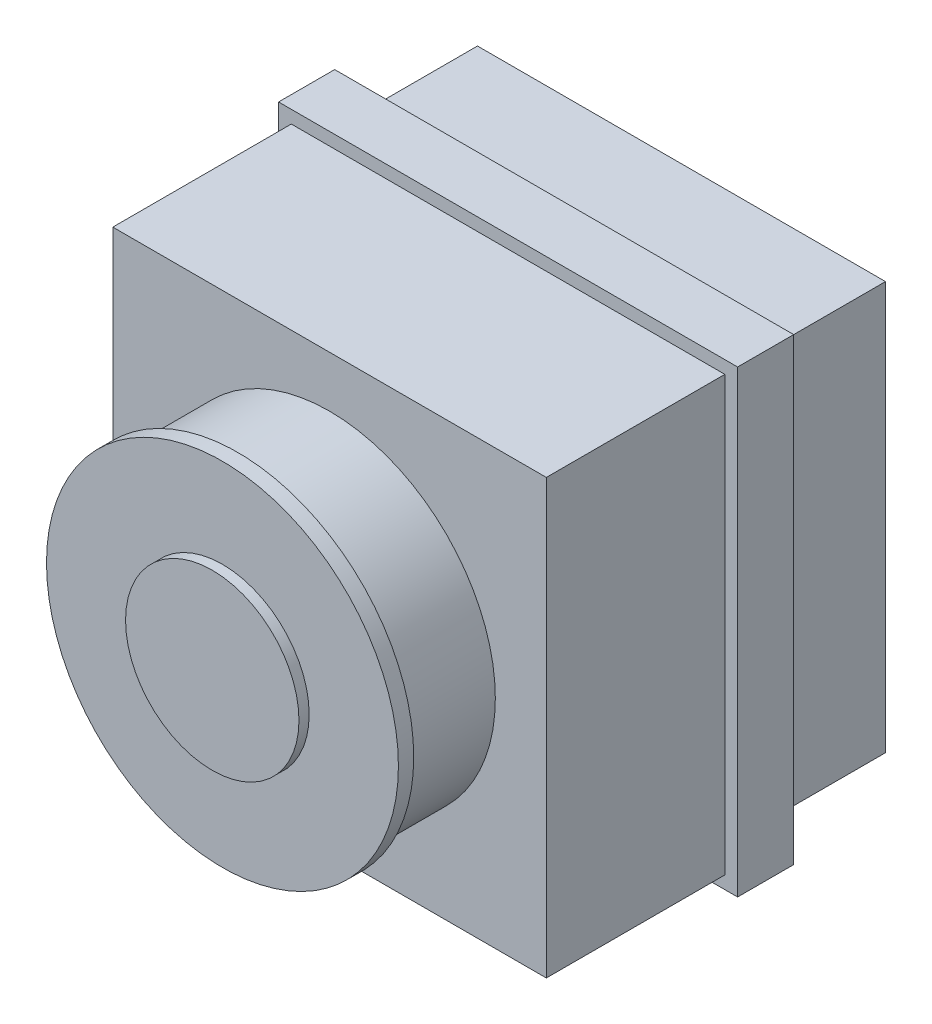
SolidWorks part; units mm, degrees
ref_plane "前基準面" through (0, 0, 0) normal (0, 0, 1) x (1, 0, 0)
ref_plane "上基準面" through (0, 0, 0) normal (0, 1, 0) x (1, 0, 0)
ref_plane "右基準面" through (0, 0, 0) normal (1, 0, 0) x (0, 0, -1)
sketch "草圖1" plane through (0, 0, 0) normal (0, 0, 1) x (1, 0, 0)
  line L0 (26, -29) -> (34, -29)
  line L1 (34, -29) -> (34, -21)
  line L2 (34, -21) -> (26, -21)
  line L3 (26, -21) -> (26, -29)
extrude "foam pad" add sketch "草圖1" along normal blind 2.3
sketch "草圖2" plane through (0, 0, 0) normal (0, 0, 1) x (1, 0, 0)
  line L0 (25.5, -29.5) -> (34.5, -29.5)
  line L1 (34.5, -29.5) -> (34.5, -20.5)
  line L2 (34.5, -20.5) -> (25.5, -20.5)
  line L3 (25.5, -20.5) -> (25.5, -29.5)
extrude "sensor PCB" add sketch "草圖2" along normal blind 1.1 from offset 2.3
sketch "草圖3" plane through (0, 0, 0) normal (0, 0, 1) x (1, 0, 0)
  line L0 (25.75, -29.25) -> (34.25, -29.25)
  line L1 (34.25, -29.25) -> (34.25, -20.75)
  line L2 (34.25, -20.75) -> (25.75, -20.75)
  line L3 (25.75, -20.75) -> (25.75, -29.25)
extrude "lens holder" add sketch "草圖3" along normal blind 3.5 from offset 3.4
sketch "草圖4" plane through (0, 0, 0) normal (0, 0, 1) x (1, 0, 0)
  circle A0 centre (30, -25) radius 3.25
extrude "lens barrel" add sketch "草圖4" along normal blind 1.8 from offset 6.9
sketch "草圖5" plane through (0, 0, 0) normal (0, 0, 1) x (1, 0, 0)
  circle A0 centre (30, -25) radius 3.45
extrude "lens ring" add sketch "草圖5" along normal blind 0.3 from offset 8.7
sketch "草圖6" plane through (0, 0, 0) normal (0, 0, 1) x (1, 0, 0)
  circle A0 centre (30, -25) radius 1.7
extrude "lens glass" add sketch "草圖6" along normal blind 0.2 from offset 9
